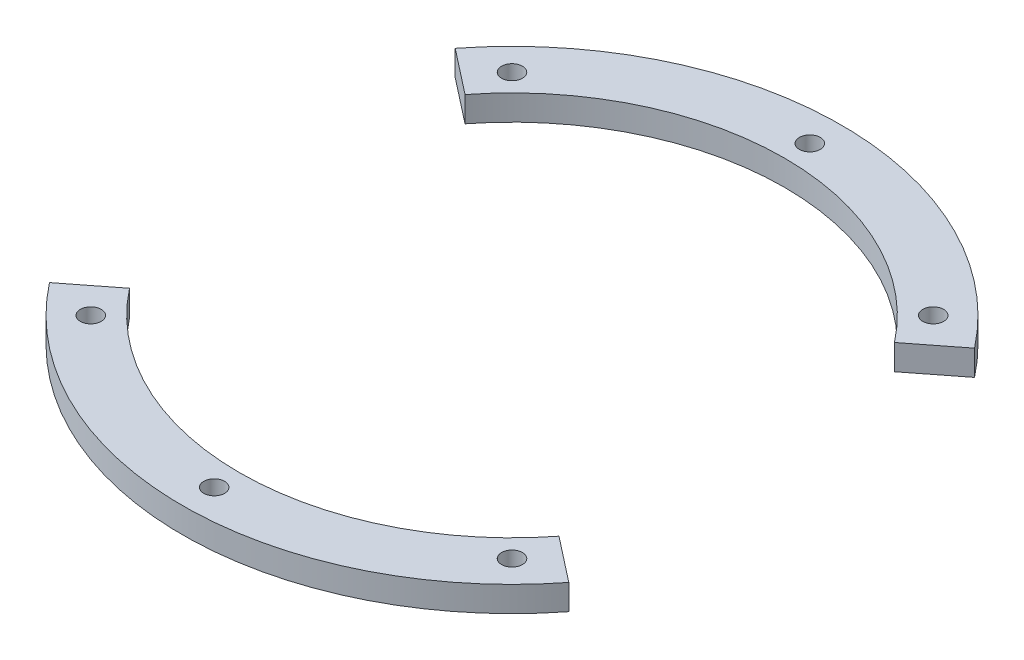
SolidWorks part; units mm, degrees
ref_plane "前视基准面" through (0, 0, 0) normal (0, 0, 1) x (1, 0, 0)
ref_plane "上视基准面" through (0, 0, 0) normal (0, 1, 0) x (1, 0, 0)
ref_plane "右视基准面" through (0, 0, 0) normal (1, 0, 0) x (0, 0, -1)
sketch "草图1" plane through (0, 0, 0) normal (0, 1, 0) x (1, 0, 0)
  circle A0 centre (0, 0) radius 43
  circle A1 centre (0, 0) radius 52
  circle A2 centre (47, 0) radius 1.65
  circle A3 centre (33.234, -33.234) radius 1.65
  circle A4 centre (0, -47) radius 1.65
  circle A5 centre (-33.234, -33.234) radius 1.65
  circle A6 centre (-47, 0) radius 1.65
  circle A7 centre (-33.234, 33.234) radius 1.65
  circle A8 centre (0, 47) radius 1.65
  circle A9 centre (33.234, 33.234) radius 1.65
  point P6 (52, 0)
  point P8 (43, 0)
  dimension "D1" = 86
  dimension "D2" = 4
  dimension "D3" = 5
  dimension "D4" = 3.3
  dimension "D5" = 8
extrude "凸台-拉伸1" add sketch "草图1" along normal blind 4
sketch "草图2" plane through (0, 4, 0) normal (0, 1, 0) x (1, 0, 0)
  line L0 (0, 0) -> (32.7612, 25.5959)
  line L1 (0, -47) -> (0, 47) construction
  line L2 (32.7612, 25.5959) -> (53.158, 41.5316)
  line L3 (0, 0) -> (26.4595, 0) construction
  line L4 (32.7612, -25.5959) -> (53.158, -41.5316)
  line L5 (0, 0) -> (32.7612, -25.5959)
  line L6 (53.158, 41.5316) -> (53.158, -41.5316)
  line L7 (0, 0) -> (0, -14.232) construction
  line L8 (-32.7612, -25.5959) -> (-53.158, -41.5316)
  line L9 (-32.7612, 25.5959) -> (-53.158, 41.5316)
  line L10 (-53.158, 41.5316) -> (-53.158, -41.5316)
  line L11 (0, 0) -> (-32.7612, -25.5959)
  line L12 (0, 0) -> (-32.7612, 25.5959)
  circle M10 centre (-47, 0) radius 1.65
  circle M12 centre (47, 0) radius 1.65
  circle M13 centre (0, 0) radius 52
  circle M14 centre (0, 0) radius 43
  dimension "D1" = 38
extrude "切除-拉伸2" cut sketch "草图2" against normal blind 10 contours L9 L10 L8 M13 | L11 L12 M14 | L12 L9 L8 L11 M14 M13 M10 | L0 L5 M14 | L5 L4 L2 L0 M14 M13 M12 | L6 L2 L4 M13
sketch "草图4" plane through (0, 4, 0) normal (0, 1, 0) x (1, 0, 0)
  line L1 (-41, -60.5354) -> (41, -60.5354)
  line L2 (-41, -60.5354) -> (-41, 60.5354)
  line L3 (-41, 60.5354) -> (41, 60.5354)
  line L4 (41, -60.5354) -> (41, 60.5354)
  line L5 (-41, -60.5354) -> (41, 60.5354) construction
  line L6 (-41, 60.5354) -> (41, -60.5354) construction
  point P0 (0, 0)
  dimension "D1" = 82
extrude "切除-拉伸-薄壁1" [suppressed] cut sketch "草图4" against normal blind 10 thin
